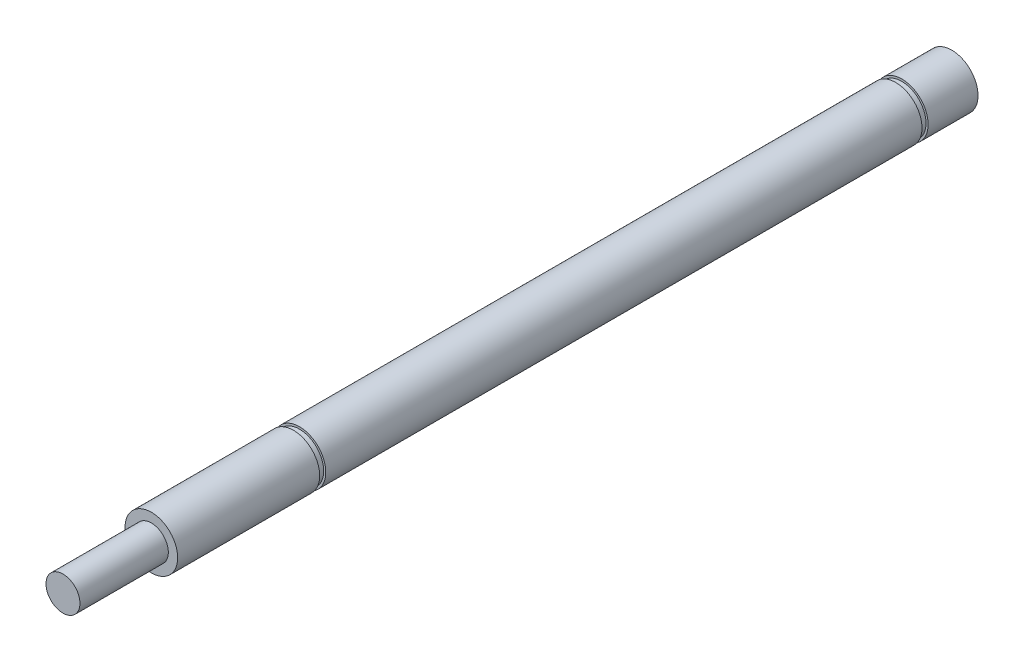
SolidWorks part; units mm, degrees
ref_plane "Front Plane" through (0, 0, 0) normal (0, 0, 1) x (1, 0, 0)
ref_plane "Top Plane" through (0, 0, 0) normal (0, 1, 0) x (1, 0, 0)
ref_plane "Right Plane" through (0, 0, 0) normal (1, 0, 0) x (0, 0, -1)
sketch "Sketch1" plane through (15.3043, 0, 0) normal (1, 0, 0) x (0, 0, -1)
  line L0 (-13.843, 26.7535) -> (-13.843, 22.6535) construction
  line L1 (-3.175, 26.7535) -> (-13.843, 26.7535) construction
  line L2 (-3.175, 27.8785) -> (-3.175, 21.5285) construction
  line L5 (13.97, 27.8785) -> (-3.175, 27.8785)
  line L6 (86.6828, 27.8785) -> (65.6556, 27.8785)
  line L9 (93.4456, 27.8785) -> (93.4456, 21.5285) construction
  line L10 (93.4456, 24.7035) -> (-13.843, 24.7035) construction
  line L11 (-13.843, 26.7535) -> (-13.843, 24.7035)
  line L12 (-3.175, 26.7535) -> (-13.843, 26.7535)
  line L13 (-3.175, 27.8785) -> (-3.175, 26.7535)
  line L20 (93.4456, 27.8785) -> (93.4456, 24.7035)
  line L21 (93.4456, 24.7035) -> (-13.843, 24.7035)
  line L28 (93.4456, 27.8785) -> (-1.5875, 27.8785) construction
  line L32 (93.4456, 27.8785) -> (87.4194, 27.8785)
  line L33 (65.6556, 27.8785) -> (14.7066, 27.8785)
  line L43 (13.97, 27.8785) -> (13.97, 27.6245) construction
  line L44 (13.97, 27.6245) -> (14.7066, 27.6245) construction
  line L45 (14.7066, 27.8785) -> (14.7066, 27.6245) construction
  line L46 (86.6828, 27.8785) -> (86.6828, 27.6245) construction
  line L47 (87.4194, 27.8785) -> (87.4194, 27.6245) construction
  line L48 (87.4194, 27.6245) -> (86.6828, 27.6245) construction
  line L49 (13.97, 27.8785) -> (13.97, 27.6245)
  line L50 (13.97, 27.6245) -> (14.7066, 27.6245)
  line L51 (14.7066, 27.8785) -> (14.7066, 27.6245)
  line L52 (86.6828, 27.8785) -> (86.6828, 27.6245)
  line L53 (87.4194, 27.8785) -> (87.4194, 27.6245)
  line L54 (87.4194, 27.6245) -> (86.6828, 27.6245)
revolve "Revolve1" add sketch "Sketch1" angle 360 about L21
